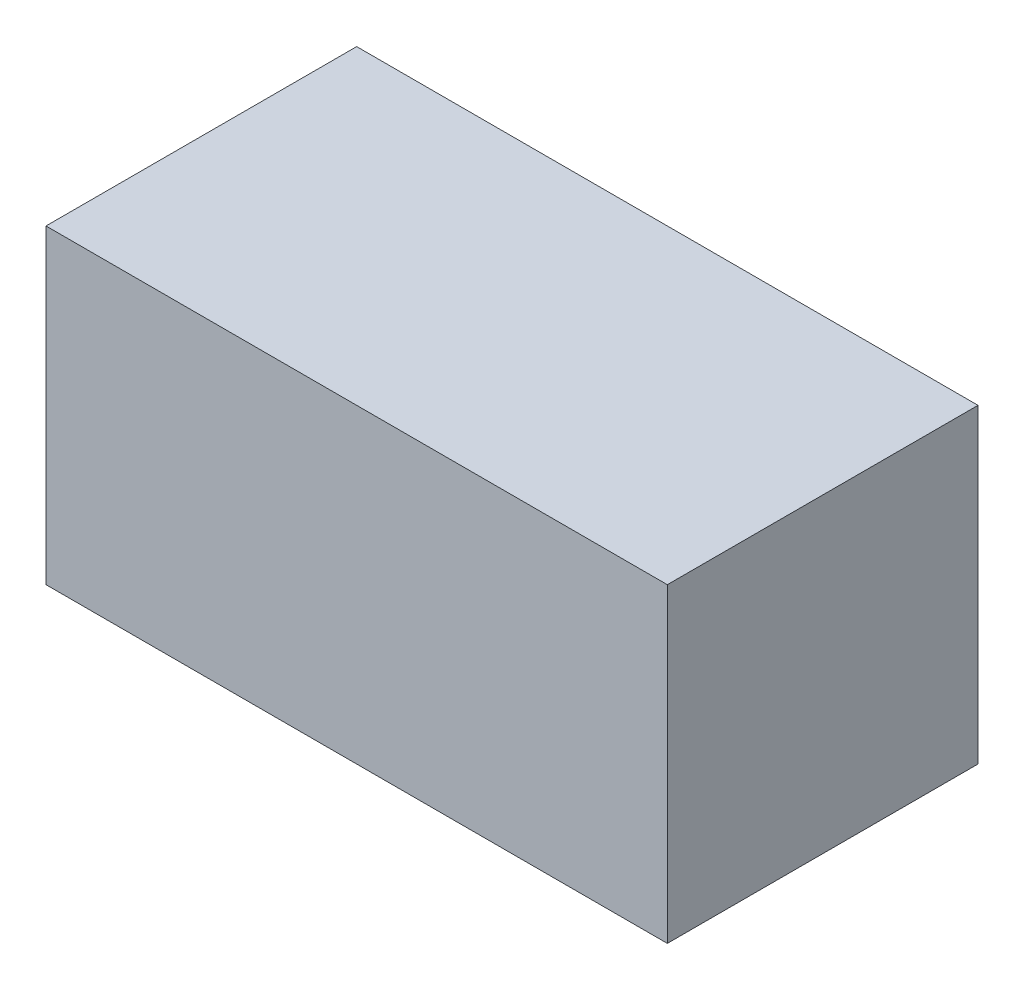
SolidWorks part; units mm, degrees
ref_plane "Front Plane" through (0, 0, 0) normal (0, 0, 1) x (1, 0, 0)
ref_plane "Top Plane" through (0, 0, 0) normal (0, 1, 0) x (1, 0, 0)
ref_plane "Right Plane" through (0, 0, 0) normal (1, 0, 0) x (0, 0, -1)
sketch "Sketch1" plane through (0, 0, 0) normal (0, 1, 0) x (1, 0, 0)
  line L1 (0, 0) -> (-304.8, 0)
  line L2 (0, 0) -> (0, 152.4)
  line L3 (0, 152.4) -> (-304.8, 152.4)
  line L4 (-304.8, 0) -> (-304.8, 152.4)
extrude "Boss-Extrude1" add sketch "Sketch1" along normal blind 152.4
